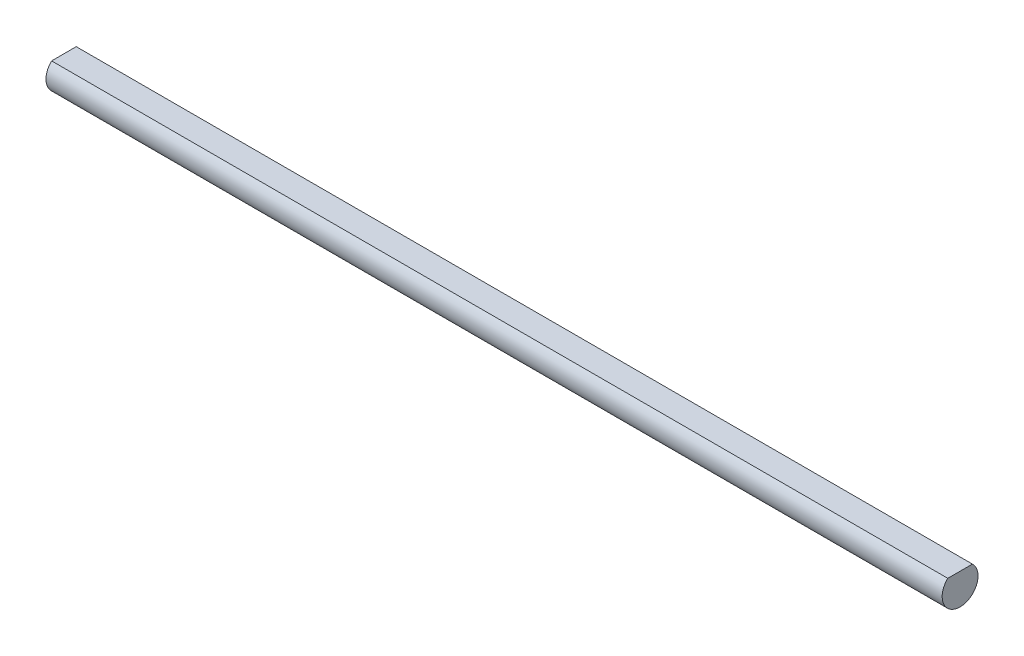
SolidWorks part; units mm, degrees
ref_plane "Ebene vorne" through (0, 0, 0) normal (0, 0, 1) x (1, 0, 0)
ref_plane "Ebene oben" through (0, 0, 0) normal (0, 1, 0) x (1, 0, 0)
ref_plane "Ebene rechts" through (0, 0, 0) normal (1, 0, 0) x (0, 0, -1)
sketch "Skizze2" plane through (0, 0, 0) normal (1, 0, 0) x (0, 0, -1)
  line L0 (0, 0) -> (-30998.062, 0) construction
  line L1 (0, 0) -> (0, -30998.062) construction
  line L2 (-2.75, 2.9047) -> (2.75, 2.9047)
  arc A0 (-2.75, 2.9047) -> (2.75, 2.9047) centre (0, 0) ccw
  dimension "D1" = 4
  dimension "D2" = 5.5
extrude "Aufsatz-Linear austragen1" add sketch "Skizze2" along normal mid plane 200
